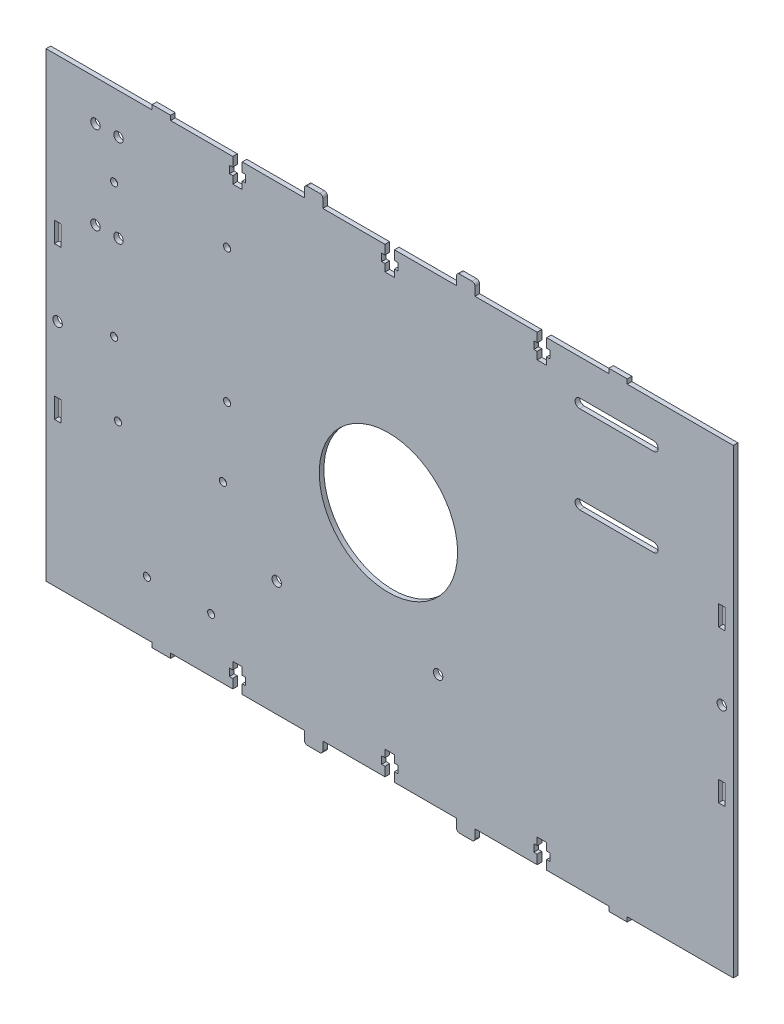
SolidWorks part; units mm, degrees
ref_plane "前视基准面" through (0, 0, 0) normal (0, 0, 1) x (1, 0, 0)
ref_plane "上视基准面" through (0, 0, 0) normal (0, 1, 0) x (1, 0, 0)
ref_plane "右视基准面" through (0, 0, 0) normal (1, 0, 0) x (0, 0, -1)
sketch "草图1" plane through (0, 0, 0) normal (0, 0, 1) x (1, 0, 0)
  line L0 (0, 0) -> (0, -4)
  line L1 (0, -4) -> (-1.45, -4)
  line L2 (-1.45, -4) -> (-1.45, -7.2)
  line L3 (-1.45, -7.2) -> (0, -7.2)
  line L4 (0, -7.2) -> (0, -10.4)
  line L5 (0, -10.4) -> (4.1, -10.4)
  line L6 (4.1, -10.4) -> (4.1, -7.2)
  line L7 (4.1, -7.2) -> (5.55, -7.2)
  line L8 (5.55, -7.2) -> (5.55, -4)
  line L9 (5.55, -4) -> (4.1, -4)
  line L10 (4.1, -4) -> (4.1, 0)
  line L11 (0, 0) -> (-26.95, 0)
  line L12 (-26.95, 0) -> (-26.95, 5)
  line L13 (-26.95, 5) -> (-34.95, 5)
  line L14 (-34.95, 5) -> (-34.95, 0)
  line L15 (2.05, -10.4) -> (2.05, -56.6) construction
  line L16 (-30.95, 5) -> (-30.95, 0) construction
  line L17 (-67.45, -4) -> (-66, -4)
  line L18 (-66, -7.2) -> (-67.45, -7.2)
  line L19 (-60.45, -7.2) -> (-61.9, -7.2)
  line L20 (-61.9, -4) -> (-60.45, -4)
  line L21 (-66, -4) -> (-66, 0)
  line L22 (-66, -10.4) -> (-66, -7.2)
  line L23 (-61.9, -10.4) -> (-66, -10.4)
  line L24 (-61.9, -7.2) -> (-61.9, -10.4)
  line L25 (-67.45, -7.2) -> (-67.45, -4)
  line L26 (-60.45, -4) -> (-60.45, -7.2)
  line L27 (-61.9, 0) -> (-61.9, -4)
  line L28 (-61.9, 0) -> (-34.95, 0)
  line L29 (31.05, 5) -> (39.05, 5)
  line L30 (31.05, 0) -> (31.05, 5)
  line L31 (39.05, 5) -> (39.05, 0)
  line L32 (4.1, 0) -> (31.05, 0)
  line L33 (66, 0) -> (39.05, 0)
  line L34 (66, 0) -> (66, -4)
  line L35 (64.55, -4) -> (64.55, -7.2)
  line L36 (71.55, -7.2) -> (71.55, -4)
  line L37 (66, -7.2) -> (66, -10.4)
  line L38 (66, -10.4) -> (70.1, -10.4)
  line L39 (70.1, -10.4) -> (70.1, -7.2)
  line L40 (70.1, -4) -> (70.1, 0)
  line L41 (66, -4) -> (64.55, -4)
  line L42 (64.55, -7.2) -> (66, -7.2)
  line L43 (70.1, -7.2) -> (71.55, -7.2)
  line L44 (71.55, -4) -> (70.1, -4)
  line L45 (68.05, -10.4) -> (68.05, -6.6) construction
  line L46 (70.1, 0) -> (97.05, 0)
  line L47 (132, 0) -> (105.05, 0)
  line L48 (97.05, 5) -> (97.05, 0)
  line L49 (105.05, 0) -> (105.05, 5)
  line L50 (105.05, 5) -> (97.05, 5)
  line L51 (-63.95, -10.4) -> (-63.95, -6.6) construction
  line L52 (-96.95, 5) -> (-96.95, 0) construction
  line L53 (-66, 0) -> (-92.95, 0)
  line L54 (-92.95, 5) -> (-92.95, 0)
  line L55 (-100.95, 5) -> (-92.95, 5)
  line L56 (-100.95, 0) -> (-100.95, 5)
  line L57 (-127.9, 0) -> (-100.95, 0)
  line L58 (2.05, -10.4) -> (-140.5, -10.4) construction
  line L59 (-127.9, 0) -> (-139.95, 0)
  line L60 (132, 0) -> (144.05, 0)
  line L64 (-139.95, 0) -> (-141.95, 0)
  line L66 (-96.95, -205) -> (-96.95, -200) construction
  line L79 (-63.95, -189.6) -> (-63.95, -193.4) construction
  line L101 (68.05, -189.6) -> (68.05, -193.4) construction
  line L102 (-30.95, -205) -> (-30.95, -200) construction
  line L103 (-127.9, -200) -> (-100.95, -200)
  line L104 (-100.95, -200) -> (-100.95, -205)
  line L137 (-141.95, 0) -> (-141.95, -200) construction
  line L138 (-141.95, -200) -> (-139.95, -200)
  line L140 (-143.35, -62.6) -> (-140.55, -62.6)
  line L141 (-143.35, -62.6) -> (-143.35, -71.4)
  line L142 (-143.35, -71.4) -> (-140.55, -71.4)
  line L143 (-140.55, -62.6) -> (-140.55, -71.4)
  line L144 (-143.35, -62.6) -> (-140.55, -71.4) construction
  line L145 (-143.35, -71.4) -> (-140.55, -62.6) construction
  line L146 (-141.95, -100) -> (-134.9383, -100) construction
  line L148 (-140.55, -137.4) -> (-140.55, -128.6)
  line L149 (-143.35, -137.4) -> (-143.35, -128.6)
  line L150 (-143.35, -128.6) -> (-140.55, -128.6)
  line L151 (-143.35, -137.4) -> (-140.55, -137.4)
  line L152 (-141.95, 0) -> (-146.95, 0)
  line L153 (-146.95, 0) -> (-146.95, -200)
  line L154 (-146.95, -200) -> (-141.95, -200)
  line L156 (146.05, -200) -> (144.05, -200)
  line L157 (151.05, -200) -> (146.05, -200)
  line L158 (144.05, 0) -> (146.05, 0)
  line L159 (146.05, 0) -> (151.05, 0)
  line L160 (151.05, 0) -> (151.05, -200)
  line L161 (146.05, -100) -> (139.0383, -100) construction
  line L162 (147.45, -71.4) -> (144.65, -62.6) construction
  line L163 (147.45, -62.6) -> (144.65, -71.4) construction
  line L164 (146.05, 0) -> (146.05, -200) construction
  line L165 (147.45, -137.4) -> (144.65, -137.4)
  line L166 (147.45, -128.6) -> (144.65, -128.6)
  line L167 (147.45, -137.4) -> (147.45, -128.6)
  line L168 (144.65, -137.4) -> (144.65, -128.6)
  line L169 (144.65, -62.6) -> (144.65, -71.4)
  line L170 (147.45, -71.4) -> (144.65, -71.4)
  line L171 (147.45, -62.6) -> (147.45, -71.4)
  line L172 (147.45, -62.6) -> (144.65, -62.6)
  line L173 (-100.95, -205) -> (-92.95, -205)
  line L174 (-92.95, -205) -> (-92.95, -200)
  line L175 (-66, -200) -> (-92.95, -200)
  line L176 (105.05, -205) -> (97.05, -205)
  line L177 (105.05, -200) -> (105.05, -205)
  line L178 (97.05, -205) -> (97.05, -200)
  line L179 (132, -200) -> (105.05, -200)
  line L180 (70.1, -200) -> (97.05, -200)
  line L181 (71.55, -196) -> (70.1, -196)
  line L182 (70.1, -192.8) -> (71.55, -192.8)
  line L183 (64.55, -192.8) -> (66, -192.8)
  line L184 (66, -196) -> (64.55, -196)
  line L185 (70.1, -196) -> (70.1, -200)
  line L186 (70.1, -189.6) -> (70.1, -192.8)
  line L187 (66, -189.6) -> (70.1, -189.6)
  line L188 (66, -192.8) -> (66, -189.6)
  line L189 (71.55, -192.8) -> (71.55, -196)
  line L190 (64.55, -196) -> (64.55, -192.8)
  line L191 (66, -200) -> (66, -196)
  line L192 (66, -200) -> (39.05, -200)
  line L193 (4.1, -200) -> (31.05, -200)
  line L194 (39.05, -205) -> (39.05, -200)
  line L195 (31.05, -200) -> (31.05, -205)
  line L196 (31.05, -205) -> (39.05, -205)
  line L197 (-61.9, -200) -> (-34.95, -200)
  line L198 (-61.9, -200) -> (-61.9, -196)
  line L199 (-60.45, -196) -> (-60.45, -192.8)
  line L200 (-67.45, -192.8) -> (-67.45, -196)
  line L201 (-61.9, -192.8) -> (-61.9, -189.6)
  line L202 (-61.9, -189.6) -> (-66, -189.6)
  line L203 (-66, -189.6) -> (-66, -192.8)
  line L204 (-66, -196) -> (-66, -200)
  line L205 (-61.9, -196) -> (-60.45, -196)
  line L206 (-60.45, -192.8) -> (-61.9, -192.8)
  line L207 (-66, -192.8) -> (-67.45, -192.8)
  line L208 (-67.45, -196) -> (-66, -196)
  line L209 (-34.95, -205) -> (-34.95, -200)
  line L210 (-26.95, -205) -> (-34.95, -205)
  line L211 (-26.95, -200) -> (-26.95, -205)
  line L212 (0, -200) -> (-26.95, -200)
  line L213 (4.1, -196) -> (4.1, -200)
  line L214 (5.55, -196) -> (4.1, -196)
  line L215 (5.55, -192.8) -> (5.55, -196)
  line L216 (4.1, -192.8) -> (5.55, -192.8)
  line L217 (4.1, -189.6) -> (4.1, -192.8)
  line L218 (0, -189.6) -> (4.1, -189.6)
  line L219 (0, -192.8) -> (0, -189.6)
  line L220 (-1.45, -192.8) -> (0, -192.8)
  line L221 (-1.45, -196) -> (-1.45, -192.8)
  line L222 (0, -196) -> (-1.45, -196)
  line L223 (0, -200) -> (0, -196)
  line L224 (-139.95, -200) -> (-127.9, -200)
  line L225 (132, -200) -> (144.05, -200)
  circle A0 centre (-141.95, -100) radius 2.05
  circle A1 centre (146.05, -100) radius 2.05
  circle A2 centre (1.5, -100) radius 30
  point P139 (-141.95, -67)
  point P166 (146.05, -67)
  dimension "D9" = 33
  dimension "D14" = 33
  dimension "D5" = 8
  dimension "D1" = 4.1
  dimension "D2" = 7
  dimension "D3" = 4
  dimension "D4" = 3.2
  dimension "D6" = 200
  dimension "D7" = 5
  dimension "D8" = 284
  dimension "D10" = 2.8
  dimension "D11" = 2
  dimension "D12" = 8.8
  dimension "D13" = 5
extrude "凸台-拉伸1" add sketch "草图1" along normal blind 2
sketch "草图2" plane through (0, 0, 0) normal (0, 1, 0) x (1, 0, 0)
  line L0 (0, -1) -> (4.1, -1)
  line L1 (0, -2) -> (0, 0) construction
  line L2 (4.1, -2) -> (4.1, 0) construction
  circle A0 centre (2.05, -1) radius 2.05
sketch "草图4" plane through (0, 0, 2) normal (0, 0, 1) x (1, 0, 0)
  line L0 (-64.9649, -178.9699) -> (-118.2649, -178.9699) construction
  line L1 (-64.9649, -178.9699) -> (-64.9649, -110.3699) construction
  line L2 (-64.9649, -110.3699) -> (-118.2649, -110.3699) construction
  line L3 (-118.2649, -178.9699) -> (-118.2649, -110.3699) construction
  line L4 (-117.4649, -35.442) -> (-117.4649, -93.442) construction
  line L5 (-117.4649, -35.442) -> (-68.4649, -35.442) construction
  line L6 (-68.4649, -35.442) -> (-68.4649, -93.442) construction
  line L7 (-117.4649, -93.442) -> (-120.9649, -93.442)
  line L8 (-120.9649, -11.942) -> (-64.9649, -11.942) construction
  line L9 (-120.9649, -11.942) -> (-120.9649, -96.942) construction
  line L10 (-120.9649, -96.942) -> (-64.9649, -96.942) construction
  line L11 (-64.9649, -11.942) -> (-64.9649, -96.942) construction
  line L12 (-68.4649, -93.442) -> (-64.9649, -93.442) construction
  line L13 (-125.55, -17.5) -> (84.45, -17.5) construction
  line L14 (84.45, -17.5) -> (116.4599, -17.5) construction
  line L15 (84.45, -15.5) -> (116.4599, -15.5)
  line L16 (84.45, -19.5) -> (116.4599, -19.5)
  line L17 (-100.95, 0) -> (-146.95, 0) construction
  line L18 (-125.55, -17.5) -> (-125.55, -55.5) construction
  line L19 (-125.55, -36.5) -> (-126.0731, -36.5) construction
  line L20 (84.45, -55.5) -> (116.4599, -55.5) construction
  line L21 (84.45, -57.5) -> (116.4599, -57.5)
  line L22 (84.45, -53.5) -> (116.4599, -53.5)
  line L23 (-140.55, -71.4) -> (-140.55, -62.6) construction
  line L24 (-103.2649, -176.4699) -> (-75.3649, -176.4699) construction
  line L25 (-115.7649, -124.3699) -> (-70.2649, -124.3699) construction
  line L26 (-66, 0) -> (-92.95, 0) construction
  line L27 (-106.587, 13.8565) -> (-89.1716, 13.8565)
  line L28 (-106.587, 13.8565) -> (-106.587, 2)
  line L29 (-106.587, 2) -> (-89.1716, 2)
  line L30 (-89.1716, 13.8565) -> (-89.1716, 2)
  line L31 (93.2832, 11.3546) -> (106.901, 11.3546)
  line L32 (93.2832, 11.3546) -> (93.2832, 2)
  line L33 (93.2832, 2) -> (106.901, 2)
  line L34 (106.901, 11.3546) -> (106.901, 2)
  line L35 (-86.3736, -222.5015) -> (-110.7948, -222.5015)
  line L36 (-86.3736, -222.5015) -> (-86.3736, -202)
  line L37 (-86.3736, -202) -> (-110.7948, -202)
  line L38 (-110.7948, -222.5015) -> (-110.7948, -202)
  line L39 (93.2832, -231.6759) -> (111.1156, -231.6759)
  line L40 (93.2832, -231.6759) -> (93.2832, -202)
  line L41 (93.2832, -202) -> (111.1156, -202)
  line L42 (111.1156, -231.6759) -> (111.1156, -202)
  line L43 (151.05, 0) -> (105.05, 0) construction
  line L44 (105.05, -200) -> (151.05, -200) construction
  line L45 (-92.95, -200) -> (-66, -200) construction
  line L46 (-120.55, -17.5) -> (-120.55, -28.2789) construction
  line L47 (23.05, -150) -> (-46.95, -150) construction
  line L48 (-146.95, 0) -> (-146.95, -200) construction
  line L49 (-26.95, -200) -> (0, -200) construction
  circle A0 centre (-75.3649, -176.4699) radius 1.55
  circle A1 centre (-103.2649, -176.4699) radius 1.55
  circle A2 centre (-70.2649, -124.3699) radius 1.55
  circle A3 centre (-115.7649, -124.3699) radius 1.55
  circle A4 centre (-117.4649, -35.442) radius 1.55
  circle A5 centre (-68.4649, -35.442) radius 1.55
  circle A6 centre (-117.4649, -93.442) radius 1.55
  circle A7 centre (-68.4649, -93.442) radius 1.55
  circle A8 centre (-125.55, -17.5) radius 2.05
  circle A9 centre (-125.55, -55.5) radius 2.05
  arc A10 (84.45, -15.5) -> (84.45, -19.5) centre (84.45, -17.5) ccw
  arc A11 (116.4599, -19.5) -> (116.4599, -15.5) centre (116.4599, -17.5) ccw
  arc A12 (84.45, -57.5) -> (84.45, -53.5) centre (84.45, -55.5) cw
  arc A13 (116.4599, -53.5) -> (116.4599, -57.5) centre (116.4599, -55.5) cw
  circle A14 centre (-115.55, -55.5) radius 2.05
  circle A15 centre (-115.55, -17.5) radius 2.05
  circle A16 centre (-46.95, -150) radius 2.05
  circle A17 centre (23.05, -150) radius 2.05
  point P31 (100.4549, -17.5)
  point P43 (100.4549, -55.5)
  dimension "D1" = 3.1
  dimension "D7" = 38
  dimension "D8" = 17.5
  dimension "D20" = 70
  dimension "D21" = 4.1
  dimension "D22" = 4.1
  dimension "D2" = 58
  dimension "D3" = 49
  dimension "D4" = 85
  dimension "D5" = 56
  dimension "D6" = 3.5
  dimension "D9" = 210
  dimension "D10" = 15
  dimension "D11" = 27.9
  dimension "D12" = 45.5
  dimension "D13" = 5.1
  dimension "D14" = 52.1
  dimension "D15" = 2
  dimension "D16" = 2
  dimension "D17" = 2
  dimension "D18" = 2
  dimension "D19" = 5
  dimension "D23" = 100
  dimension "D24" = 50
extrude "切除-拉伸1" cut sketch "草图4" against normal blind 10
fillet "圆角1" radius 1.3 8 edges at (39.05, 5, 1) (31.05, 5, 1) (-26.95, 5, 1) (-34.95, 5, 1) (39.05, -205, 1) (-26.95, -205, 1) (31.05, -205, 1) (-34.95, -205, 1)
